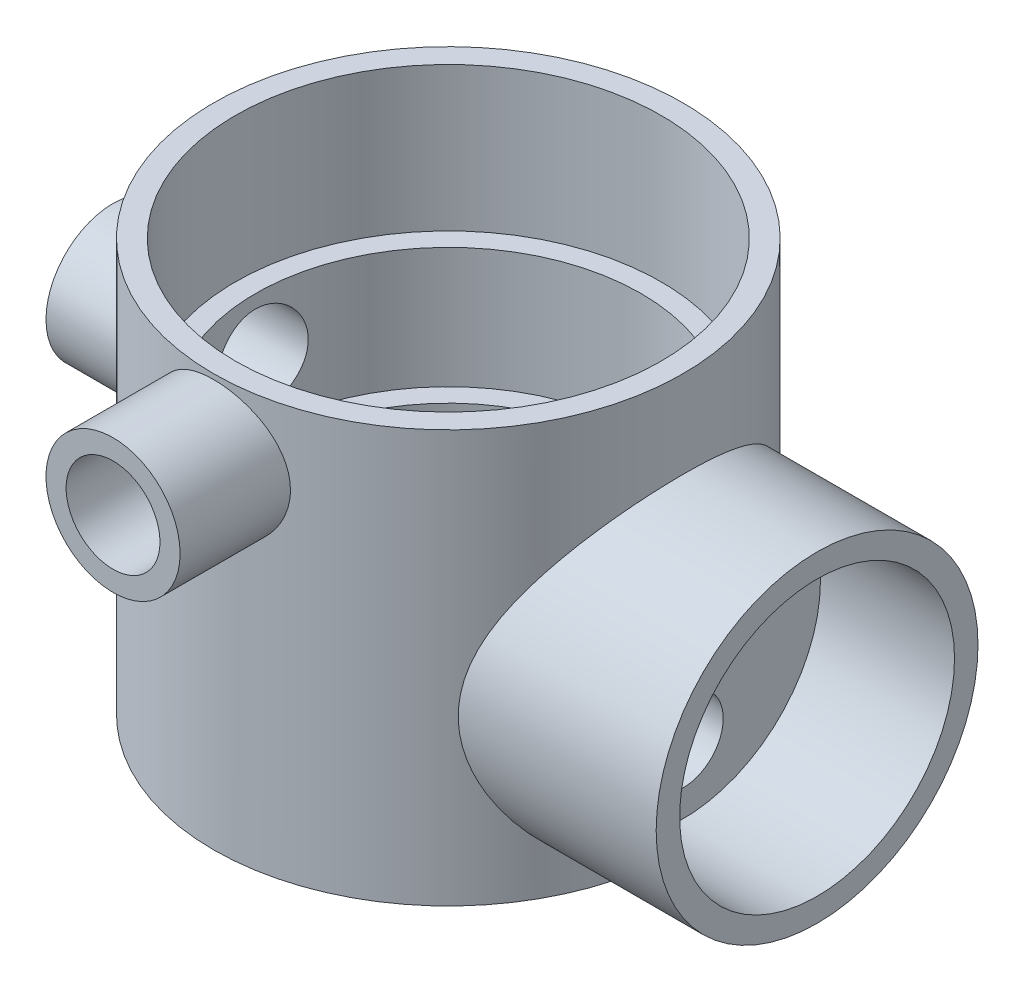
SolidWorks part; units mm, degrees
material "Acrylic (Medium-high impact)"
ref_plane "Front Plane" through (0, 0, 0) normal (0, 0, 1) x (1, 0, 0)
ref_plane "Top Plane" through (0, 0, 0) normal (0, 1, 0) x (1, 0, 0)
ref_plane "Right Plane" through (0, 0, 0) normal (1, 0, 0) x (0, 0, -1)
sketch "Sketch1" plane through (0, 0, 0) normal (0, 1, 0) x (1, 0, 0)
  circle A0 centre (0, 0) radius 35
extrude "Base" add sketch "Sketch1" along normal blind 4
sketch "Sketch2" plane through (0, 4, 0) normal (0, 1, 0) x (1, 0, 0)
  circle A0 centre (0, 0) radius 7.5
  dimension "D1" = 15
extrude "Centering boss" add sketch "Sketch2" along normal blind 2
sketch "Sketch3" plane through (0, 4, 0) normal (0, 1, 0) x (1, 0, 0)
  circle A0 centre (0, 0) radius 25.75
  circle A1 centre (0, 0) radius 35
  dimension "D1" = 51.5
extrude "Inlet tier" add sketch "Sketch3" along normal blind 18
sketch "Sketch4" plane through (0, 22, 0) normal (0, 1, 0) x (1, 0, 0)
  circle A0 centre (0, 0) radius 28.75
  circle A1 centre (0, 0) radius 35
  dimension "D1" = 57.5
extrude "Patient tier" add sketch "Sketch4" along normal blind 18
sketch "Sketch5" plane through (0, 40, 0) normal (0, 1, 0) x (1, 0, 0)
  circle A0 centre (0, 0) radius 31.75
  circle A1 centre (0, 0) radius 35
  dimension "D1" = 63.5
extrude "Outlet tier" add sketch "Sketch5" along normal blind 21.5
ref_plane "Plane1" through (55, 0, 0) normal (1, 0, 0) x (0, 0, -1)
sketch "Sketch7" plane through (55, 0, 0) normal (1, 0, 0) x (0, 0, -1)
  line L1 (-35, 0) -> (35, 0) construction
  circle A1 centre (0, 24.5) radius 24
  dimension "D1" = 48
  dimension "D2" = 24.5
extrude "Inlet" add sketch "Sketch7" against normal up to next contours A1
sketch "Sketch10" plane through (55, 0, 0) normal (1, 0, 0) x (0, 0, -1)
  circle A0 centre (0, 24.5) radius 20.5
  dimension "D1" = 41
extrude "Inlet ID" cut sketch "Sketch10" against normal blind 20
sketch "Sketch11" plane through (35, 0, 0) normal (1, 0, 0) x (0, 0, -1)
  line L0 (-35, 0) -> (35, 0) construction
  circle A0 centre (0, 14) radius 6
  dimension "D1" = 14
extrude "Inlet pass thru" cut sketch "Sketch11" against normal up to next
ref_plane "Plane4" through (-50, 0, 0) normal (1, 0, 0) x (0, 0, -1)
sketch "Sketch12" plane through (-50, 0, 0) normal (1, 0, 0) x (0, 0, -1)
  circle A1 centre (0, 31) radius 10
  dimension "D1" = 20
extrude "Boss-Extrude8" add sketch "Sketch12" along normal up to next
sketch "Sketch13" plane through (-50, 0, 0) normal (-1, 0, 0) x (0, 0, 1)
  circle A0 centre (0, 31) radius 7
extrude "Cut-Extrude3" cut sketch "Sketch13" against normal up to next
ref_plane "Plane5" through (0, 0, 50) normal (0, 0, 1) x (1, 0, 0)
sketch "Sketch14" plane through (0, 0, 50) normal (0, 0, 1) x (1, 0, 0)
  line L0 (35, 61.5) -> (-35, 61.5) construction
  circle A0 centre (0, 50.75) radius 10
  dimension "D1" = 10.75
  dimension "D2" = 20
extrude "Boss-Extrude9" add sketch "Sketch14" against normal up to surface (16.459 mm away) contours A0
sketch "Sketch15" plane through (0, 0, 50) normal (0, 0, 1) x (1, 0, 0)
  circle A0 centre (0, 50.75) radius 7
extrude "Cut-Extrude4" cut sketch "Sketch15" against normal up to next
